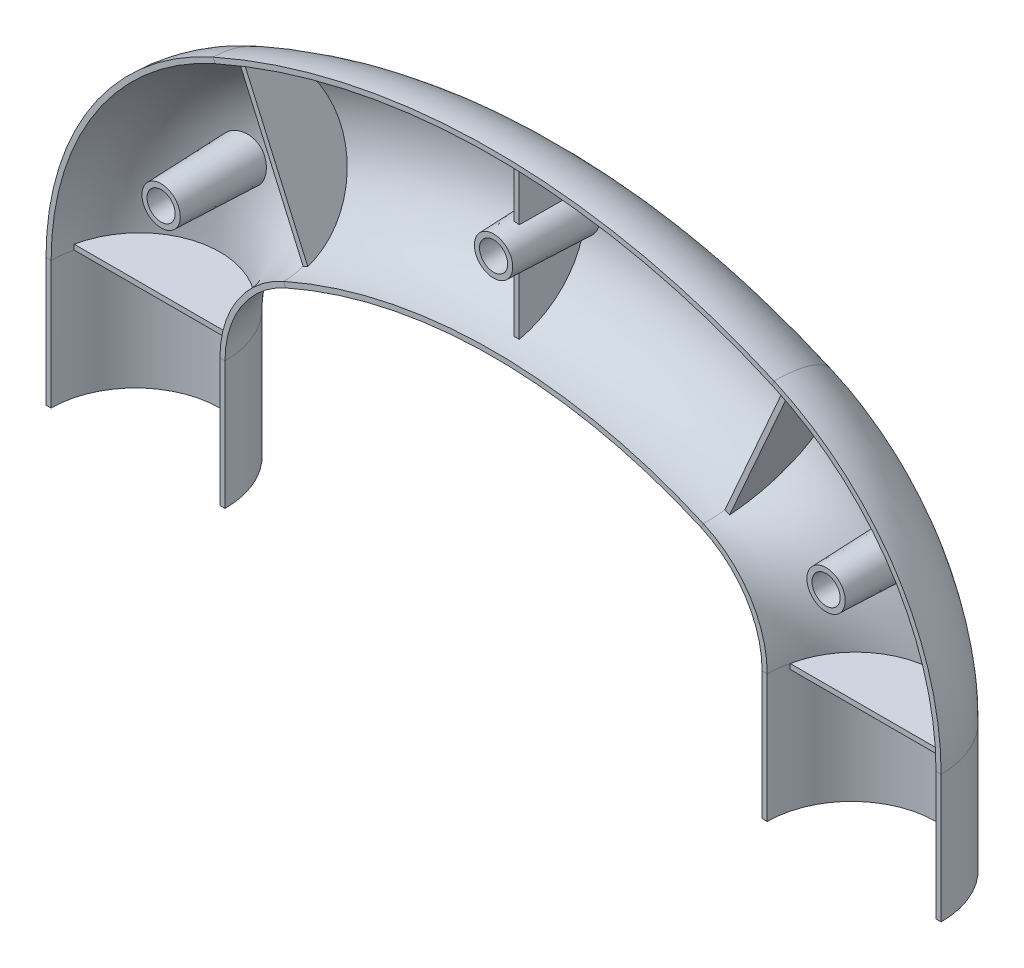
SolidWorks part; units mm, degrees
ref_plane "Front Plane" through (0, 0, 0) normal (0, 0, 1) x (1, 0, 0)
ref_plane "Top Plane" through (0, 0, 0) normal (0, 1, 0) x (1, 0, 0)
ref_plane "Right Plane" through (0, 0, 0) normal (1, 0, 0) x (0, 0, -1)
sketch "Sketch1" plane through (0, 0, 0) normal (0, 1, 0) x (1, 0, 0)
  line L0 (-222.25, 0) -> (-219.71, 0)
  line L1 (-135.89, 0) -> (-133.35, 0)
  arc A0 (-133.35, 0) -> (-222.25, 0) centre (-177.8, 0) ccw
  arc A1 (-135.89, 0) -> (-219.71, 0) centre (-177.8, 0) ccw
  dimension "D1" = 2.54
  dimension "D2" = 88.9
  dimension "D3" = 133.35
sketch "Sketch2" plane through (0, 0, 0) normal (0, 0, 1) x (1, 0, 0)
  line L0 (-133.35, 0) -> (-133.35, 63.5)
  line L1 (-135.89, 0) -> (-133.35, 0) construction
  line L2 (133.35, 63.5) -> (133.35, 0)
  arc A0 (-133.35, 63.5) -> (-103.1875, 109.9191) centre (-82.55, 63.5) cw
  arc A1 (-103.1875, 109.9191) -> (103.1875, 109.9191) centre (0, -122.1764) cw
  arc A2 (103.1875, 109.9191) -> (133.35, 63.5) centre (82.55, 63.5) cw
  dimension "D2" = 50.8
  dimension "D3" = 254
  dimension "D4" = 50.8
  dimension "D1" = 63.5
  dimension "D5" = 266.7
sketch "Sketch3" plane through (0, 0, 0) normal (0, 0, 1) x (1, 0, 0)
  line L0 (-133.35, 0) -> (-222.25, 0) construction
  circle A0 centre (-165.1, 114.3) radius 9.525
  circle A1 centre (0, 175.26) radius 9.525
  circle A2 centre (165.1, 114.3) radius 9.525
  circle A3 centre (-165.1, 114.3) radius 6.985
  circle A4 centre (0, 175.26) radius 6.985
  circle A5 centre (165.1, 114.3) radius 6.985
  dimension "D1" = 19.05
  dimension "D2" = 19.05
  dimension "D3" = 19.05
  dimension "D4" = 114.3
  dimension "D5" = 165.1
  dimension "D6" = 175.26
  dimension "D7" = 165.1
  dimension "D8" = 114.3
  dimension "D9" = 2.54
ref_plane "Plane1" through (0, 0, -10.16) normal (0, 0, 1) x (1, 0, 0)
sketch "Sketch5" plane through (0, 0, -10.16) normal (0, 0, 1) x (1, 0, 0)
  line L0 (-135.89, 63.5) -> (-219.71, 63.5)
  line L1 (-103.1875, 109.9191) -> (-104.2114, 112.2436) construction
  line L2 (-104.2114, 112.2436) -> (-138.0001, 188.9516)
  line L3 (103.1875, 109.9191) -> (104.2114, 112.2436) construction
  line L4 (104.2114, 112.2436) -> (138.0001, 188.9516)
  line L5 (135.89, 63.5) -> (219.71, 63.5)
  line L6 (0, 134.366) -> (0, 165.862)
  line L7 (0, 184.912) -> (0, 218.186)
  dimension "D1" = 83.82
  dimension "D2" = 2.54
  dimension "D3" = 2.54
  dimension "D4" = 83.82
  dimension "D5" = 76.708
  dimension "D6" = 76.708
  dimension "D7" = 83.82
  dimension "D8" = 2.54
  dimension "D9" = 83.82
  dimension "D10" = 2.54
  dimension "D11" = 134.366
  dimension "D12" = 31.496
  dimension "D13" = 33.274
  dimension "D14" = 19.05
sweep "Sweep1" add profiles "Sketch1" path "Sketch2"
extrude "Extrude-Thin2" add sketch "Sketch5" against normal up to next draft 2 thin contours L0 | L2 | L7 | L6 | L4 | L5
extrude "Boss-Extrude1" add sketch "Sketch3" against normal up to next draft 2 contours A3 | A4 | A5 | A0 | A1 | A2
